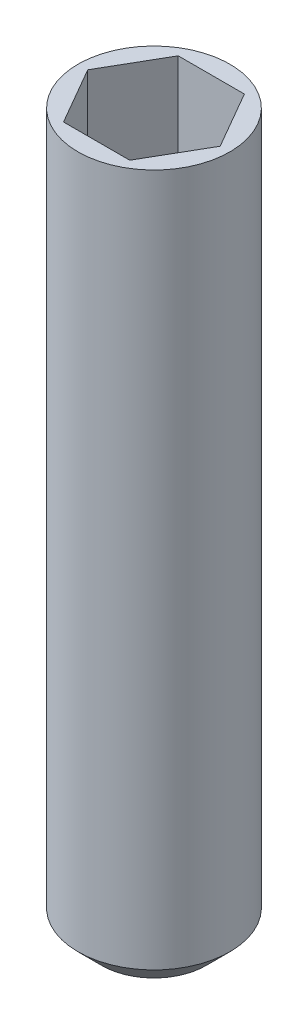
SolidWorks part; units mm, degrees
material "Cast Alloy Steel"
ref_plane "Front Plane" through (0, 0, 0) normal (0, 0, 1) x (1, 0, 0)
ref_plane "Top Plane" through (0, 0, 0) normal (0, 1, 0) x (1, 0, 0)
ref_plane "Right Plane" through (0, 0, 0) normal (1, 0, 0) x (0, 0, -1)
sketch "Sketch1" plane through (0, 0, 0) normal (0, 1, 0) x (1, 0, 0)
  circle A0 centre (0, 0) radius 2.0193
  dimension "D1" = 4.0386
extrude "Boss-Extrude1" add sketch "Sketch1" against normal blind 19.05
chamfer "Chamfer1" distance 0.635 angle 45 1 edges at (0, -19.05, 2.0193)
sketch "Sketch2" plane through (0, 0, 0) normal (0, 1, 0) x (1, 0, 0)
  line L1 (-1.7598, 0) -> (-0.8799, -1.524)
  line L2 (-0.8799, -1.524) -> (0.8799, -1.524)
  line L3 (0.8799, -1.524) -> (1.7598, 0)
  line L4 (1.7598, 0) -> (0.8799, 1.524)
  line L5 (0.8799, 1.524) -> (-0.8799, 1.524)
  line L6 (-0.8799, 1.524) -> (-1.7598, 0)
  circle A0 centre (0, 0) radius 1.524 construction
  dimension "D1" = 3.048
extrude "Cut-Extrude1" cut sketch "Sketch2" against normal blind 2.54
